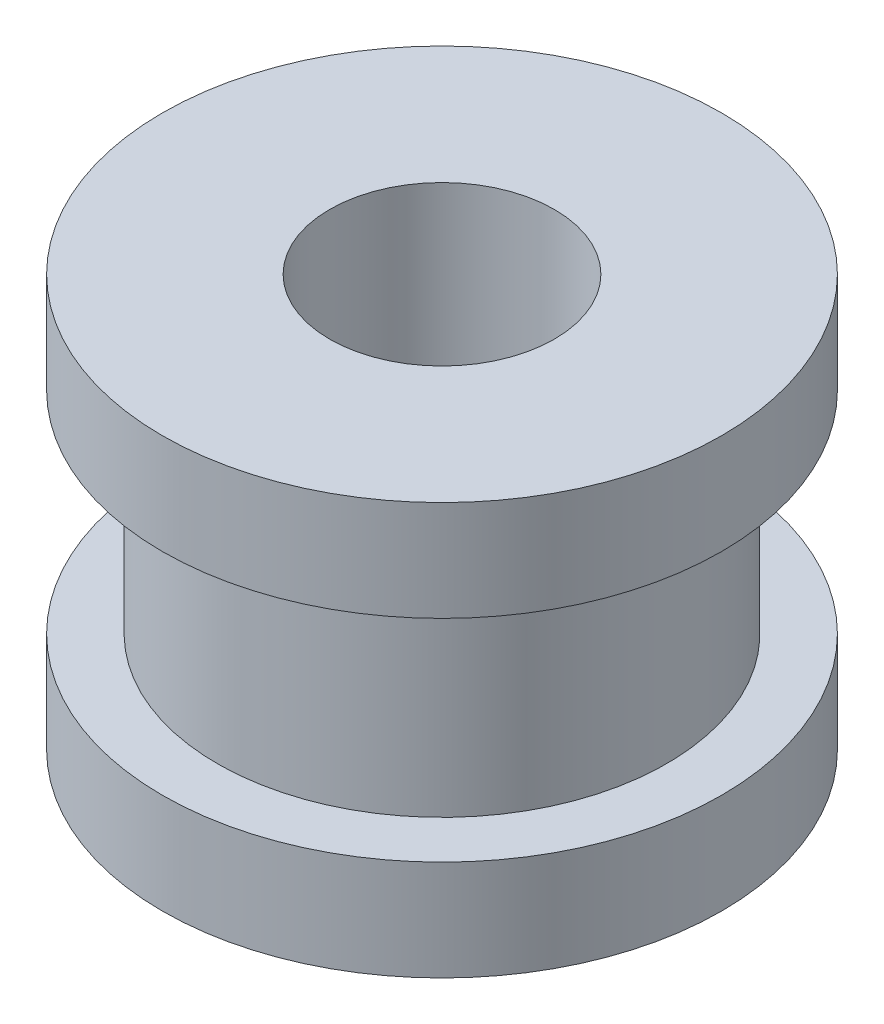
SolidWorks part; units mm, degrees
ref_plane "Plan de face" through (0, 0, 0) normal (0, 0, 1) x (1, 0, 0)
ref_plane "Plan de dessus" through (0, 0, 0) normal (0, 1, 0) x (1, 0, 0)
ref_plane "Plan de droite" through (0, 0, 0) normal (1, 0, 0) x (0, 0, -1)
sketch "Esquisse1" plane through (0, 0, 0) normal (0, 0, 1) x (1, 0, 0)
  line L0 (0, 0) -> (-1, 0)
  line L1 (-1, 0) -> (-1, 1.83)
  line L2 (-1, 1.83) -> (0, 1.83)
  line L3 (0, 1.83) -> (0, 5.68)
  line L4 (0, 5.68) -> (-1, 5.68)
  line L5 (-1, 5.68) -> (-1, 7.51)
  line L6 (-1, 7.51) -> (2.05, 7.51)
  line L7 (4.1, 7.51) -> (4.1, 0) construction
  line L8 (0, 0) -> (2.05, 0)
  line L9 (2.05, 0) -> (2.05, 7.51)
  dimension "D1" = 3.85
  dimension "D2" = 1.83
  dimension "D3" = 1.83
  dimension "D4" = 1
  dimension "D5" = 1
  dimension "D6" = 4.1
  dimension "D7" = 2.05
revolve "Révolution1" add sketch "Esquisse1" angle 360 about L7
